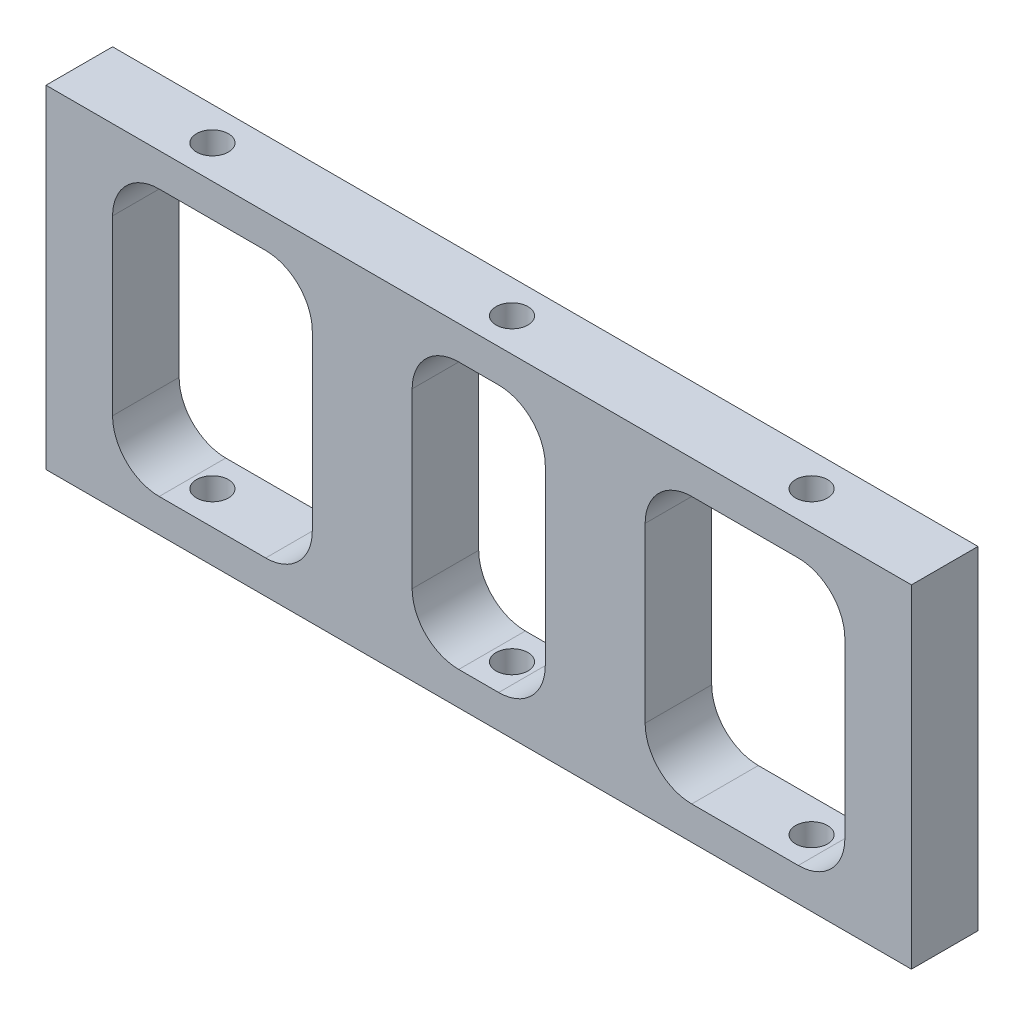
SolidWorks part; units mm, degrees
ref_plane "Plan de face" through (0, 0, 0) normal (0, 0, 1) x (1, 0, 0)
ref_plane "Plan de dessus" through (0, 0, 0) normal (0, 1, 0) x (1, 0, 0)
ref_plane "Plan de droite" through (0, 0, 0) normal (1, 0, 0) x (0, 0, -1)
sketch "Esquisse1" plane through (0, 0, 0) normal (0, 0, 1) x (1, 0, 0)
  line L0 (0, 0) -> (130, 0)
  line L1 (0, 0) -> (0, 50)
  line L2 (130, 0) -> (130, 50)
  line L3 (0, 50) -> (130, 50)
  line L4 (10, 5) -> (10, 45)
  line L5 (10, 5) -> (120, 5)
  line L6 (10, 45) -> (120, 45)
  line L7 (120, 5) -> (120, 45)
  line L8 (65, 50) -> (65, 0) construction
  line L9 (40, 45) -> (55, 45)
  line L10 (100, 50) -> (100, 0) construction
  line L11 (40, 45) -> (40, 5)
  line L12 (30, 50) -> (30, 0) construction
  line L13 (55, 45) -> (55, 5)
  line L14 (40, 5) -> (55, 5)
  line L15 (75, 5) -> (90, 5)
  line L16 (75, 5) -> (75, 45)
  line L17 (90, 5) -> (90, 45)
  line L18 (75, 45) -> (90, 45)
  dimension "D1" = 130
  dimension "D2" = 50
  dimension "D3" = 30
  dimension "D4" = 30
  dimension "D5" = 10
  dimension "D6" = 5
  dimension "D7" = 5
  dimension "D8" = 10
  dimension "D9" = 10
  dimension "D10" = 10
  dimension "D11" = 10
  dimension "D12" = 10
extrude "Boss.-Extru.1" add sketch "Esquisse1" along normal blind 10 contours L3 L1 L0 L2 L7 L5 L4 L6 | L13 L6 L11 L5 | L5 L17 L6 L16
sketch "Esquisse2" plane through (0, 50, 0) normal (0, 1, 0) x (1, 0, 0)
  line L0 (0, -5) -> (130, -5) construction
  line L1 (0, -10) -> (0, 0) construction
  line L2 (130, -10) -> (130, 0) construction
  line L3 (130, -5) -> (65, 0) construction
  line L4 (0, 0) -> (130, 0) construction
  line L5 (65, 0) -> (65, -10) construction
  line L6 (0, -10) -> (130, -10) construction
  circle A0 centre (20, -5) radius 2.4
  circle A1 centre (65, -5) radius 2.4
  circle A2 centre (110, -5) radius 2.4
  dimension "D1" = 4.8
  dimension "D2" = 4.8
  dimension "D3" = 4.8
  dimension "D4" = 20
  dimension "D5" = 20
extrude "Enlèv. mat.-Extru.1" cut sketch "Esquisse2" against normal through all
fillet "Congé1" radius 7 12 edges at (120, 45, 5) (90, 45, 5) (120, 5, 5) (90, 5, 5) (75, 5, 5) (75, 45, 5) (55, 45, 5) (55, 5, 5) (40, 45, 5) (40, 5, 5) (10, 5, 5) (10, 45, 5)
